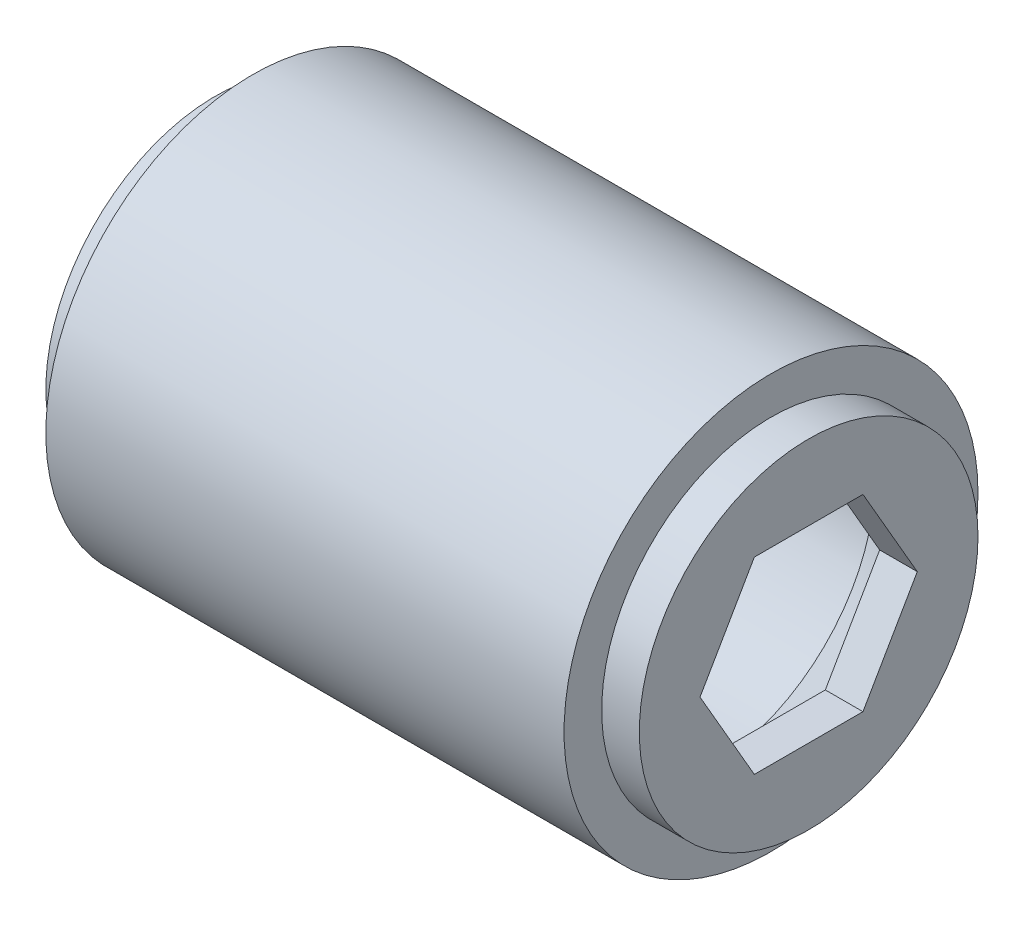
SolidWorks part; units mm, degrees
ref_plane "Front Plane" through (0, 0, 0) normal (0, 0, 1) x (1, 0, 0)
ref_plane "Top Plane" through (0, 0, 0) normal (0, 1, 0) x (1, 0, 0)
ref_plane "Right Plane" through (0, 0, 0) normal (1, 0, 0) x (0, 0, -1)
sketch "Sketch4" plane through (0, 0, 0) normal (0, 0, 1) x (1, 0, 0)
  line L0 (0, 0) -> (-4.1633, 0) construction
  line L1 (-29.54, 11) -> (-2, 11)
  line L3 (-26.0759, 9) -> (-5.4641, 9)
  line L5 (-29.54, 9) -> (-29.54, 11)
  line L6 (-29.54, 9) -> (-31.54, 9)
  line L7 (-29.54, 9) -> (-29.54, 7) construction
  line L8 (-29.54, 7) -> (-31.54, 7) construction
  line L9 (-31.54, 9) -> (-31.54, 7)
  line L10 (-2, 9) -> (0, 9)
  line L12 (-2, 7) -> (0, 7) construction
  line L13 (0, 9) -> (0, 7)
  line L14 (-29.54, 7) -> (-26.0759, 9)
  line L15 (-2, 7) -> (-5.4641, 9)
  line L16 (0, 7) -> (0, 0)
  line L17 (-2, 9) -> (-2, 11)
  line L18 (0, 0) -> (-2, 0)
  line L19 (-2, 0) -> (-2, 7)
  line L20 (-31.54, 7) -> (-31.54, 0)
  line L21 (-31.54, 0) -> (-29.54, 0)
  line L22 (-29.54, 0) -> (-29.54, 7)
  dimension "D1" = 2
  dimension "D2" = 9
  dimension "D3" = 30
  dimension "D4" = 2
  dimension "D5" = 2
  dimension "D6" = 2
  dimension "D7" = 2
  dimension "D8" = 2
  dimension "D9" = 30
  dimension "D10" = 27.54
revolve "Revolve2" add sketch "Sketch4" angle 360 about L0
sketch "Sketch5" plane through (-31.54, 0, 0) normal (-1, 0, 0) x (0, 0, 1)
  line L1 (-2.8868, 5) -> (-5.7735, 0)
  line L2 (-5.7735, 0) -> (-2.8868, -5)
  line L3 (-2.8868, -5) -> (2.8868, -5)
  line L4 (2.8868, -5) -> (5.7735, 0)
  line L5 (5.7735, 0) -> (2.8868, 5)
  line L6 (2.8868, 5) -> (-2.8868, 5)
  circle A0 centre (0, 0) radius 5 construction
  dimension "D1" = 10
extrude "Cut-Extrude1" cut sketch "Sketch5" against normal through all
